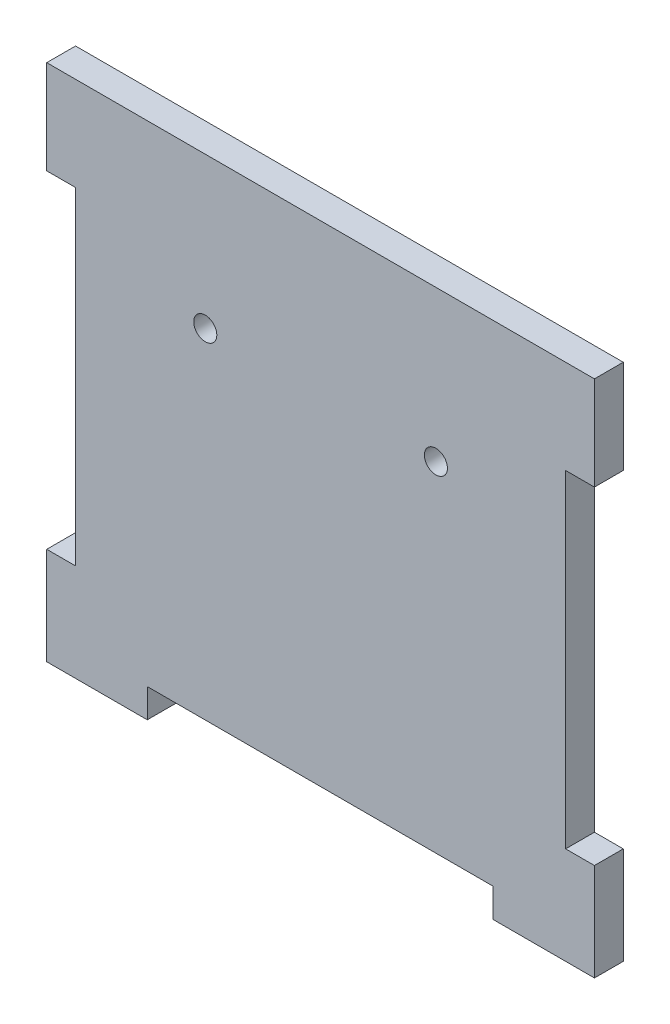
SolidWorks part; units mm, degrees
ref_plane "Ebene vorne" through (0, 0, 0) normal (0, 0, 1) x (1, 0, 0)
ref_plane "Ebene oben" through (0, 0, 0) normal (0, 1, 0) x (1, 0, 0)
ref_plane "Ebene rechts" through (0, 0, 0) normal (1, 0, 0) x (0, 0, -1)
sketch "Skizze1" plane through (0, 0, 0) normal (0, 0, 1) x (1, 0, 0)
  line L0 (-61.3783, 63.8192) -> (-56.3783, 63.8192)
  line L1 (-61.3783, 80.0783) -> (33.6217, 80.0783)
  line L2 (-61.3783, 80.0783) -> (-61.3783, 63.8192)
  line L3 (-61.3783, -9.9217) -> (-43.9395, -9.9217)
  line L4 (33.6217, 80.0783) -> (33.6217, 63.8192)
  line L5 (28.6217, 75.0783) -> (-56.3783, 75.0783)
  line L6 (28.6217, 75.0783) -> (28.6217, -4.9217)
  line L7 (28.6217, -4.9217) -> (-56.3783, -4.9217)
  line L8 (-56.3783, 75.0783) -> (-56.3783, -4.9217)
  line L9 (28.6217, 75.0783) -> (-56.3783, -4.9217) construction
  line L10 (28.6217, -4.9217) -> (-56.3783, 75.0783) construction
  line L11 (-56.3783, 6.9771) -> (-61.3783, 6.9771)
  line L12 (28.6217, 6.9771) -> (33.6217, 6.9771)
  line L13 (28.6217, 63.8192) -> (33.6217, 63.8192)
  line L14 (33.6217, 6.9771) -> (33.6217, -9.9217)
  line L15 (-61.3783, 6.9771) -> (-61.3783, -9.9217)
  line L16 (-43.9395, -4.9217) -> (-43.9395, -9.9217)
  line L17 (16.0605, -4.9217) -> (16.0605, -9.9217)
  line L18 (16.0605, -9.9217) -> (33.6217, -9.9217)
  circle A0 centre (-33.8783, 53.9019) radius 2
  circle A1 centre (6.1217, 53.9019) radius 2
  point P0 (-13.8783, 35.0783)
  point P5 (-13.9395, 35.3982)
  point P14 (-13.8783, 35.0783)
  dimension "D1" = 95
  dimension "D2" = 90
  dimension "D5" = 5
  dimension "D6" = 5
  dimension "D7" = 5
  dimension "D8" = 5
extrude "Aufsatz-Linear austragen1" add sketch "Skizze1" along normal blind 5
